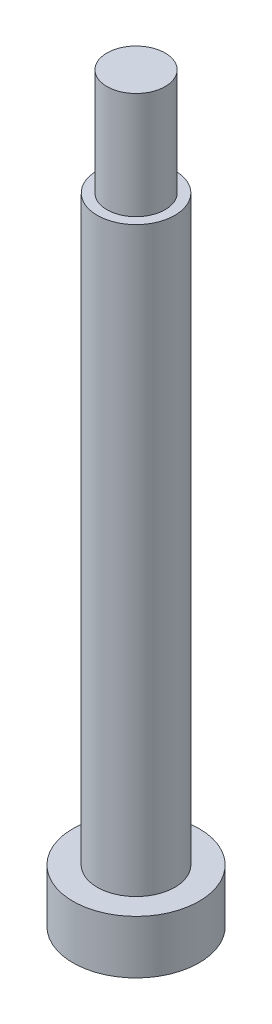
SolidWorks part; units mm, degrees
ref_plane "前视基准面" through (0, 0, 0) normal (0, 0, 1) x (1, 0, 0)
ref_plane "上视基准面" through (0, 0, 0) normal (0, 1, 0) x (1, 0, 0)
ref_plane "右视基准面" through (0, 0, 0) normal (1, 0, 0) x (0, 0, -1)
sketch "草图1" plane through (0, 0, 0) normal (0, 1, 0) x (1, 0, 0)
  circle A0 centre (0, 0) radius 4
  dimension "D1" = 8
extrude "凸台-拉伸1" add sketch "草图1" along normal blind 60
sketch "草图2" plane through (0, 60, 0) normal (0, 1, 0) x (1, 0, 0)
  circle A0 centre (0, 0) radius 3
  dimension "D1" = 6
extrude "凸台-拉伸2" add sketch "草图2" along normal blind 11
cosmetic thread "装饰螺纹线1" parameters "D1"=6, "D2"=4.917
sketch "草图3" plane through (0, 0, 0) normal (0, -1, 0) x (1, 0, 0)
  circle A0 centre (0, 0) radius 6.5
  dimension "D1" = 13
extrude "凸台-拉伸3" add sketch "草图3" along normal blind 5.5
